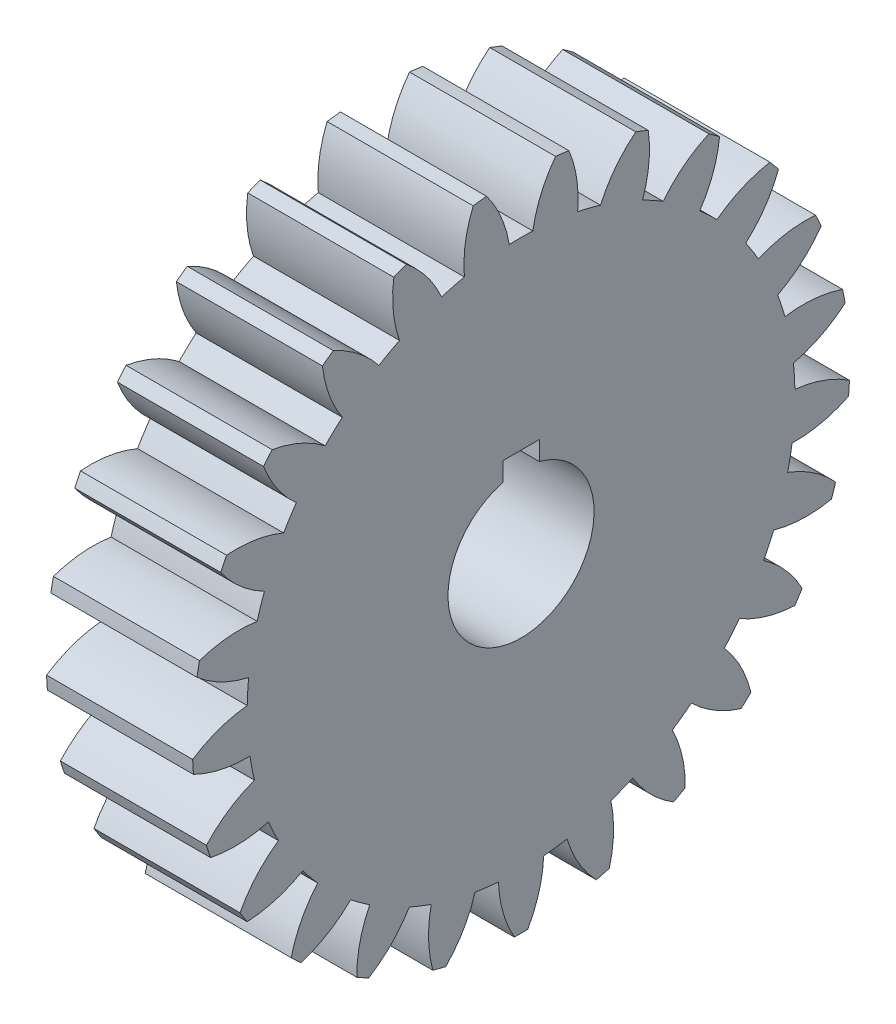
SolidWorks part; units mm, degrees
ref_plane "Plane1" through (0, 0, 0) normal (0, 0, 1) x (1, 0, 0)
ref_plane "Plane2" through (0, 0, 0) normal (0, 1, 0) x (1, 0, 0)
ref_plane "Plane3" through (0, 0, 0) normal (1, 0, 0) x (0, 0, -1)
sketch "HoldingSke" plane through (0, 0, 0) normal (0, 1, 0) x (1, 0, 0)
  line L0 (0, 0) -> (138.1213, -64.407)
  line L1 (-15, 0) -> (100, 0) construction
  line L2 (0, 0) -> (-2.1039, 2.3779)
  line L3 (0, 0) -> (-11.863, 4.5341)
  line L4 (0, 0) -> (7.8269, 3.6497)
  line L5 (0, 0) -> (-47.5972, -17.7524)
  line L6 (0, 0) -> (-21.0557, -14.2063)
  line L7 (-2.1039, 2.3779) -> (8.8308, 51.9871)
  line L8 (-76.2, 54.61) -> (-47.9044, 54.61)
  line L9 (-71.009, 38.7566) -> (-53.1078, 45.2721)
  line L10 (-76.2, 71.12) -> (104.1128, 71.12)
  line L11 (0, 0) -> (-25.4, 0)
  line L12 (-76.2, 101.6) -> (-76.0298, 101.6)
  line L13 (24.9733, 27.94) -> (52.9518, 28.4284)
  line L14 (24.9733, 27.94) -> (24.9746, 27.94)
  line L15 (24.9733, 27.94) -> (100.4006, 29.5858)
  circle A0 centre (0, 0) radius 12.7
  circle A1 centre (0, 0) radius 38.1
  circle A2 centre (0, 0) radius 38.1
  circle A3 centre (0, 0) radius 12.7
  dimension "MHD" = 76.2
  dimension "Hub_dia" = 76.2
  dimension "Bore" = 25.4
  dimension "MBD" = 25.4
  dimension "Num_teeth" = 25
  dimension "Pitch" = 152.4
  dimension "Overall_len" = 50.8
  dimension "Show_teeth" = 25
  dimension "Thickness" = 25.4
  dimension "OAL" = 50.8001
  dimension "T_dim" = 28.2956
  dimension "Ap" = 20
  dimension "H" = 19.05
  dimension "Pitch_radius" = 180.3128
  dimension "Width" = 25.4
  dimension "Backlash" = 0.1702
  dimension "Addendum_fac" = 1
  dimension "Dedendum_fac" = 1.25
  dimension "Clearance_fac" = 0.25
  dimension "Dedendum_add" = 0.0013
sketch "BasProSke" plane through (0, 0, 0) normal (0, 1, 0) x (1, 0, 0)
  line L0 (-10, 0) -> (60, 0) construction
  line L1 (0, 0) -> (0, 57.15)
  line L2 (0, 0) -> (25.4, 0)
  line L3 (25.4, 0) -> (25.4, 57.15)
  line L4 (25.4, 57.15) -> (0, 57.15)
  dimension "Thickness" = 25.4
  dimension "Diameter" = 114.3
revolve "Base-Revolve" add sketch "BasProSke" angle 360 about L0
sketch "TooCutSke" plane through (0, 0, 0) normal (1, 0, 0) x (0, 0, -1)
  line L1 (0, 0) -> (0, 107) construction
  line L2 (0, 0) -> (-3.6204, 52.7927) construction
  line L3 (0, 0) -> (-13.2427, 104.8271) construction
  line L4 (-3.6204, 52.7927) -> (-6.6214, 52.4136) construction
  arc A0 (2.0475, 47.5797) -> (-2.0475, 47.5797) centre (0, 0) ccw
  arc A1 (6.0226, 56.8573) -> (-6.0226, 56.8573) centre (0, 0) ccw
  circle A2 centre (0, 0) radius 52.9167 construction
  circle A3 centre (0, 0) radius 49.7254 construction
  arc A4 (-2.0475, 47.5797) -> (-6.0226, 56.8573) centre (-22.93, 44.1229) ccw
  arc A5 (6.0226, 56.8573) -> (2.0475, 47.5797) centre (22.93, 44.1229) ccw
  dimension "Root_dia" = 95.2475
  dimension "Overcut_dia" = 114.3508
  dimension "Pitch_dia" = 105.8333
  dimension "Base_dia" = 99.4508
  dimension "Flank_rad" = 21.1667
  dimension "Half_ang" = 7.2
  dimension "Half_CT" = 3.0248
extrude "ToothCut" cut sketch "TooCutSke" along normal through all
fillet "Breaks" [suppressed] radius 0.0847
fillet "RootFillets" [suppressed] radius 1.0596
pattern_circular "TeethCuts" count 25 every 14.4 about axis through (-10, 0, 0) along (1, 0, 0) of "ToothCut", "RootFillets", "Breaks"
sketch "HubNeaOneSke" plane through (0, 0, 0) normal (-1, 0, 0) x (0, 0, 1)
  circle A0 centre (0, 0) radius 38.1
  dimension "Diameter" = 76.2
extrude "HubNearOne" [suppressed] add sketch "HubNeaOneSke" along normal blind 25.4001
sketch "HubNeaBotSke" plane through (0, 0, 0) normal (-1, 0, 0) x (0, 0, 1)
  circle A0 centre (0, 0) radius 38.1
  dimension "Diameter" = 76.2
extrude "HubNearBoth" [suppressed] add sketch "HubNeaBotSke" along normal blind 12.7
ref_plane "FarPln" through (25.4, 0, 0) normal (1, 0, 0) x (0, 0, -1)
sketch "HubFarSke" plane through (25.4, 0, 0) normal (1, 0, 0) x (0, 0, -1)
  circle A0 centre (0, 0) radius 38.1
  dimension "Diameter" = 76.2
extrude "HubFar" [suppressed] add sketch "HubFarSke" along normal blind 12.7
sketch "BorSke" plane through (0, 0, 0) normal (1, 0, 0) x (0, 0, -1)
  circle A0 centre (0, 0) radius 12.7
  dimension "Diameter" = 25.4
extrude "Bore" cut sketch "BorSke" along normal mid plane 101.6001
sketch "KeySke" plane through (0, 0, 0) normal (1, 0, 0) x (0, 0, -1)
  line L0 (-3.175, 0) -> (-3.175, 15.5956)
  line L1 (-3.175, 15.5956) -> (3.175, 15.5956)
  line L2 (3.175, 15.5956) -> (3.175, 0)
  line L3 (0, 0) -> (0, 34) construction
  line L4 (-3.175, 0) -> (3.175, 0)
  dimension "Offset" = 15.5956
  dimension "Width" = 6.35
extrude "Keyway" cut sketch "KeySke" along normal mid plane 101.6001
pattern_circular "Keyway2" [suppressed] count 2 every 90 about axis through (-10, 0, 0) along (1, 0, 0)
equation "' \"Pitch@HoldingSke\" = 4"
equation "' \"Num_teeth@HoldingSke\" = 12"
equation "' \"Ap@HoldingSke\" =  20"
equation "' \"Ap@HoldingSke\" = 20"
equation "' \"Width@HoldingSke\" = 0.5"
equation "' \"Hub_dia@HoldingSke\"= 1"
equation "' \"Hub_dia@HoldingSke\" = 1"
equation "' \"Overall_len@HoldingSke\" = 1.0"
equation "' \"Bore@HoldingSke\" = 0.75"
equation "' \"T_dim@HoldingSke\" = 0.85"
equation "' \"Width@KeySke\" = 0.25"
equation "' \"Show_teeth@HoldingSke\" = 13"
equation "' \"Backlash@HoldingSke\" = 0.009"
equation "' \"Addendum_fac@HoldingSke\" = 1.0"
equation "' \"Dedendum_fac@HoldingSke\" = 1.25"
equation "' \"Dedendum_add@HoldingSke\" = 0.00005"
equation "' \"Clearance_fac@HoldingSke\" = 0.25"
equation "' \"Pitch@HoldingSke\" = 0.5"
equation "' \"Num_teeth@HoldingSke\" = 23"
equation "' \"Show_teeth@HoldingSke\" = 23"
equation "' \"Backlash@HoldingSke\" = 0.0375"
equation "\"Overcut_dia@TooCutSke\" = (\"Num_teeth@HoldingSke\" + 2 * \"Addendum_fac@HoldingSke\") / \"Pitch@HoldingSke\" + 0.002"
equation "\"Pitch_dia@TooCutSke\" = \"Num_teeth@HoldingSke\" / \"Pitch@HoldingSke\""
equation "\"Base_dia@TooCutSke\" = \"Num_teeth@HoldingSke\" / \"Pitch@HoldingSke\" * cos((\"Ap@HoldingSke\"  * 3.14159265 / 180))"
equation "\"Root_dia@TooCutSke\" = (\"Num_teeth@HoldingSke\" + 2) / \"Pitch@HoldingSke\" - 2 * (\"Addendum_fac@HoldingSke\" + \"Dedendum_fac@HoldingSke\") / \"Pitch@HoldingSke\" - \"Dedendum_add@HoldingSke\" * 2"
equation "\"Half_ang@TooCutSke\" = 180 / \"Num_teeth@HoldingSke\""
equation "\"Half_CT@TooCutSke\" = \"Num_teeth@HoldingSke\" / \"Pitch@HoldingSke\" * sin((3.14159265 / 2 / \"Num_teeth@HoldingSke\")) / 2 - 7 * \"Backlash@HoldingSke\" / 4"
equation "\"Flank_rad@TooCutSke\" = \"Num_teeth@HoldingSke\" / \"Pitch@HoldingSke\" / 5"
equation "\"Radius@RootFillets\" = \"Clearance_fac@HoldingSke\" / \"Pitch@HoldingSke\" + \"Dedendum_add@HoldingSke\""
equation "\"Break_rad@Breaks\" = 0.02 / \"Pitch@HoldingSke\""
equation "\"Thickness@HoldingSke\" = \"Width@HoldingSke\""
equation "\"OAL@HoldingSke\" = \"Thickness@HoldingSke\""
equation "\"MHD@HoldingSke\" = (\"Num_teeth@HoldingSke\" + 2) / \"Pitch@HoldingSke\" - 2 * (\"Addendum_fac@HoldingSke\" + \"Dedendum_fac@HoldingSke\")  / \"Pitch@HoldingSke\" - \"Dedendum_add@HoldingSke\" * 2"
equation "\"MBD@HoldingSke\" = (\"Num_teeth@HoldingSke\" + 2) / \"Pitch@HoldingSke\" - 2 * (\"Addendum_fac@HoldingSke\" + \"Dedendum_fac@HoldingSke\")  / \"Pitch@HoldingSke\" - \"Dedendum_add@HoldingSke\" * 2 - 0.002"
equation "\"MHD@HoldingSke\" = ((sgn( \"MHD@HoldingSke\" - \"Hub_dia@HoldingSke\" )-1)*( \"MHD@HoldingSke\" - \"Hub_dia@HoldingSke\" ))/-2+ \"Hub_dia@HoldingSke\""
equation "\"MBD@HoldingSke\" = ((sgn( \"MBD@HoldingSke\" - \"Bore@HoldingSke\" )-1)*( \"MBD@HoldingSke\" - \"Bore@HoldingSke\" ))/-2+ \"Bore@HoldingSke\""
equation "\"OAL@HoldingSke\" = ((sgn( \"OAL@HoldingSke\" - \"Overall_len@HoldingSke\" )+1)*( \"OAL@HoldingSke\" - \"Overall_len@HoldingSke\" ))/2 + \"Overall_len@HoldingSke\" + 0.000002"
equation "\"Num_teeth@TeethCuts\" = int( \"Show_teeth@HoldingSke\" ) + 1"
equation "\"Num_teeth@TeethCuts\" = ((sgn( \"Num_teeth@TeethCuts\" - \"Num_teeth@HoldingSke\" )-1)*( \"Num_teeth@TeethCuts\" - \"Num_teeth@HoldingSke\" ))/-2+ \"Num_teeth@HoldingSke\""
equation "\"Num_teeth@TeethCuts\" = ((sgn( \"Num_teeth@TeethCuts\" - 2.0)+1)*( \"Num_teeth@TeethCuts\" - 2.0))/2 +2.0"
equation "\"Angle@TeethCuts\" = 360.0 / \"Num_teeth@HoldingSke\""
equation "\"Diameter@BasProSke\" = (\"Num_teeth@HoldingSke\" + 2 * \"Addendum_fac@HoldingSke\") / \"Pitch@HoldingSke\""
equation "\"Thickness@BasProSke\"  = \"Thickness@HoldingSke\""
equation "' \"Fillet_rad@BasProSke\" =  \"Thickness@HoldingSke\" * 0.05"
equation "' \"Fillet_rad@BasProSke\" = \"Thickness@HoldingSke\" * 0.05"
equation "\"MHD@HoldingSke\" = ((sgn( \"MHD@HoldingSke\" - \"Root_dia@TooCutSke\" )-1)*( \"MHD@HoldingSke\" - \"Root_dia@TooCutSke\" ))/-2+ \"Root_dia@TooCutSke\""
equation "\"Diameter@HubNeaOneSke\" = \"MHD@HoldingSke\""
equation "\"Length@HubNearOne\" = \"OAL@HoldingSke\" - \"Thickness@BasProSke\""
equation "\"Diameter@HubNeaBotSke\" = \"MHD@HoldingSke\""
equation "\"Length@HubNearBoth\" = ( \"OAL@HoldingSke\" - \"Thickness@BasProSke\" ) / 2.0"
equation "\"Thickness@FarPln\" = \"Thickness@BasProSke\""
equation "\"Diameter@HubFarSke\" = \"MHD@HoldingSke\""
equation "\"Length@HubFar\" = ( \"OAL@HoldingSke\" - \"Thickness@BasProSke\" ) / 2.0"
equation "\"Diameter@BorSke\" = \"MBD@HoldingSke\""
equation "\"D1@Bore\" = \"OAL@HoldingSke\" * 2.0"
equation "\"D1@Keyway\" = \"OAL@HoldingSke\" * 2.0"
equation "\"Offset@KeySke\" = \"T_dim@HoldingSke\" - \"MBD@HoldingSke\" / 2.0"
